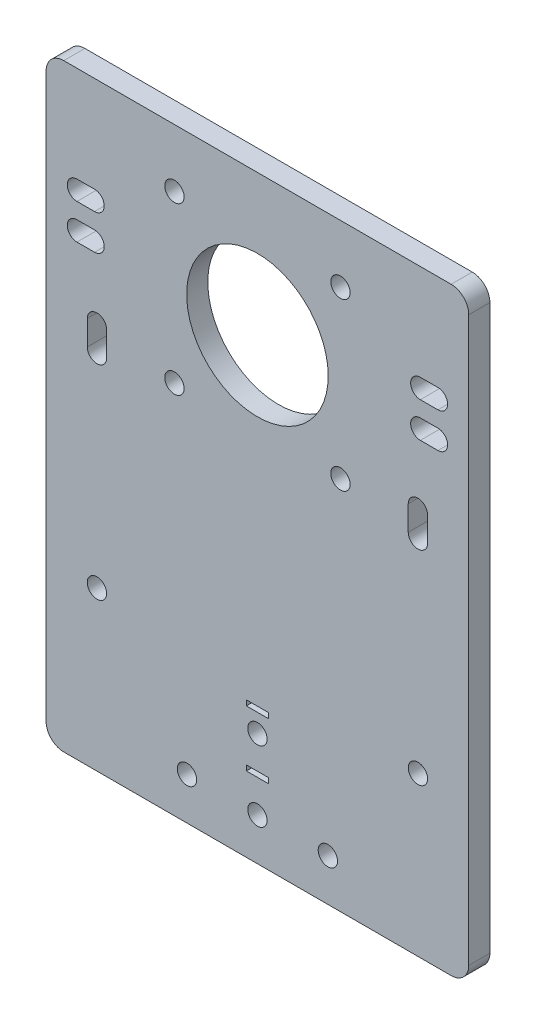
SolidWorks part; units mm, degrees
material "PET"
ref_plane "Front Plane" through (0, 0, 0) normal (0, 0, 1) x (1, 0, 0)
ref_plane "Top Plane" through (0, 0, 0) normal (0, 1, 0) x (1, 0, 0)
ref_plane "Right Plane" through (0, 0, 0) normal (1, 0, 0) x (0, 0, -1)
sketch "Sketch1" plane through (0, 0, 0) normal (0, 0, 1) x (1, 0, 0)
  line L1 (-55, -85) -> (55, -85)
  line L2 (-60, -80) -> (-60, 80)
  line L3 (-55, 85) -> (55, 85)
  line L4 (60, -80) -> (60, 80)
  line L5 (-60, -85) -> (60, 85) construction
  line L6 (-60, 85) -> (60, -85) construction
  arc A0 (-55, -85) -> (-60, -80) centre (-55, -80) cw
  arc A1 (55, -85) -> (60, -80) centre (55, -80) ccw
  arc A2 (55, 85) -> (60, 80) centre (55, 80) cw
  arc A3 (-60, 80) -> (-55, 85) centre (-55, 80) cw
  point P0 (0, 0)
  dimension "D3" = 5
  dimension "D1" = 170
  dimension "D2" = 120
extrude "Boss-Extrude1" add sketch "Sketch1" along normal blind 6
sketch "Sketch3" plane through (0, 0, 6) normal (0, 0, 1) x (1, 0, 0)
  line L0 (55, 85) -> (-55, 85) construction
  circle A0 centre (0, 45) radius 20.1
  point P6 (0, 85)
  dimension "D1" = 40
  dimension "D2" = 40.2
extrude "Cut-Extrude1" cut sketch "Sketch3" against normal blind 6
hole_wizard "M5 Clearance Hole1" positions "Sketch8" profile "Sketch9" hole size "M5" standard "ANSI Metric" end condition through all
sketch "Sketch8" plane through (0, 0, 6) normal (0, 0, 1) x (1, 0, 0)
  circle A0 centre (0, 45) radius 20.1 construction
  point P0 (-23.57, 68.57)
  point P2 (23.57, 68.57)
  point P4 (23.57, 21.43)
  point P6 (-23.57, 21.43)
  dimension "D2" = 23.57
  dimension "D3" = 23.57
  dimension "D4" = 23.57
  dimension "D5" = 23.57
  dimension "D1" = 23.57
sketch "Sketch9" plane through (-23.57, 68.57, 6) normal (1, 0, 0) x (0, -1, 0)
  line L0 (0, 0) -> (0, 6)
  line L1 (0, 6) -> (2.75, 6)
  line L2 (2.75, 6) -> (2.75, 0)
  line L5 (2.75, 0) -> (0, 0)
  line L11 (0, -6.35) -> (0, 107.95) construction
  dimension "Thru Hole Dia." = 5.5
  dimension "Thru Hole Depth" = 6
sketch "Sketch11" plane through (0, 0, 6) normal (0, 0, 1) x (1, 0, 0)
  line L0 (-45.57, 24.93) -> (-45.57, 17.93) construction
  line L1 (-42.82, 24.93) -> (-42.82, 17.93)
  line L2 (-48.32, 24.93) -> (-48.32, 17.93)
  line L5 (0, 63.1141) -> (0, -86.0691) construction
  line L8 (45.57, 24.93) -> (45.57, 17.93) construction
  line L9 (42.82, 24.93) -> (42.82, 17.93)
  line L10 (48.32, 24.93) -> (48.32, 17.93)
  arc A0 (-42.82, 24.93) -> (-48.32, 24.93) centre (-45.57, 24.93) ccw
  arc A1 (-48.32, 17.93) -> (-42.82, 17.93) centre (-45.57, 17.93) ccw
  circle A3 centre (-23.57, 21.43) radius 2.75 construction
  arc A4 (42.82, 24.93) -> (48.32, 24.93) centre (45.57, 24.93) cw
  arc A5 (48.32, 17.93) -> (42.82, 17.93) centre (45.57, 17.93) cw
  point P2 (-45.57, 21.43)
  point P15 (45.57, 21.43)
  dimension "D2" = 2.75
  dimension "D1" = 7
  dimension "D3" = 22
extrude "Cut-Extrude2" cut sketch "Sketch11" against normal blind 6
sketch "Sketch15" plane through (0, 0, 6) normal (0, 0, 1) x (1, 0, 0)
  line L0 (-51.25, 45) -> (-46.25, 45) construction
  line L1 (-51.25, 47.75) -> (-46.25, 47.75)
  line L2 (-51.25, 42.25) -> (-46.25, 42.25)
  line L3 (-51.25, 55) -> (-46.25, 55) construction
  line L4 (-51.25, 57.75) -> (-46.25, 57.75)
  line L5 (-51.25, 52.25) -> (-46.25, 52.25)
  line L6 (-60, 80) -> (-60, -80) construction
  line L8 (55, 85) -> (-55, 85) construction
  line L9 (0, 75.2932) -> (0, -13.323) construction
  line L10 (0, 63.1141) -> (0, -86.0691) construction
  line L11 (51.25, 45) -> (46.25, 45) construction
  line L12 (51.25, 47.75) -> (46.25, 47.75)
  line L13 (51.25, 42.25) -> (46.25, 42.25)
  line L14 (51.25, 55) -> (46.25, 55) construction
  line L15 (51.25, 57.75) -> (46.25, 57.75)
  line L16 (51.25, 52.25) -> (46.25, 52.25)
  arc A0 (-51.25, 47.75) -> (-51.25, 42.25) centre (-51.25, 45) ccw
  arc A1 (-46.25, 42.25) -> (-46.25, 47.75) centre (-46.25, 45) ccw
  arc A2 (-51.25, 57.75) -> (-51.25, 52.25) centre (-51.25, 55) ccw
  arc A3 (-46.25, 52.25) -> (-46.25, 57.75) centre (-46.25, 55) ccw
  arc A5 (51.25, 47.75) -> (51.25, 42.25) centre (51.25, 45) cw
  arc A6 (46.25, 42.25) -> (46.25, 47.75) centre (46.25, 45) cw
  arc A7 (51.25, 57.75) -> (51.25, 52.25) centre (51.25, 55) cw
  arc A8 (46.25, 52.25) -> (46.25, 57.75) centre (46.25, 55) cw
  point P2 (-48.75, 45)
  point P7 (-48.75, 55)
  point P15 (-54, 45)
  point P32 (48.75, 45)
  point P39 (48.75, 55)
  dimension "D1" = 30
  dimension "D2" = 2.75
  dimension "D4" = 5
  dimension "D5" = 6
  dimension "D6" = 10
extrude "Cut-Extrude4" cut sketch "Sketch15" against normal blind 6
hole_wizard "M5 Clearance Hole3" positions "Sketch17" profile "Sketch18" hole size "M5" standard "ANSI Metric" end condition through all
sketch "Sketch17" plane through (0, 0, 6) normal (0, 0, 1) x (1, 0, 0)
  line L1 (-55, -85) -> (55, -85) construction
  line L2 (60, -80) -> (60, 80) construction
  line L3 (-60, 80) -> (-60, -80) construction
  point P0 (-45.57, -39.97)
  point P2 (45.57, -39.97)
  point P4 (20, -73)
  point P6 (0, -73)
  point P8 (-20, -73)
  dimension "D3" = 40
  dimension "D1" = 61.4
  dimension "D2" = 12
  dimension "D4" = 40
sketch "Sketch18" plane through (-45.57, -39.97, 6) normal (1, 0, 0) x (0, -1, 0)
  line L0 (0, 0) -> (0, 6)
  line L1 (0, 6) -> (2.75, 6)
  line L2 (2.75, 6) -> (2.75, 0)
  line L5 (2.75, 0) -> (0, 0)
  line L11 (0, -6.35) -> (0, 107.95) construction
  dimension "Thru Hole Dia." = 5.5
  dimension "Thru Hole Depth" = 6
hole_wizard "M5 Clearance Hole2" positions "Sketch19" profile "Sketch20" hole size "M5" standard "ANSI Metric"
sketch "Sketch19" plane through (0, 0, 0) normal (0, 0, -1) x (-1, 0, 0)
  circle A0 centre (0, -73) radius 2.75 construction
  point P0 (0, -53)
  dimension "D1" = 20
sketch "Sketch20" plane through (0, -53, 0) normal (1, 0, 0) x (0, 1, 0)
  line L0 (0, 0) -> (0, 11.6524)
  line L1 (0, 11.6524) -> (2.75, 10)
  line L2 (2.75, 10) -> (2.75, 0)
  line L5 (2.75, 0) -> (0, 0)
  line L10 (0, 11.6524) -> (-2.75, 10) construction
  line L11 (0, -6.35) -> (0, 107.95) construction
  dimension "Hole Dia." = 5.5
  dimension "Hole Depth" = 10
  dimension "Drill Angle" = 118
sketch "Sketch21" plane through (0, 0, 0) normal (0, 0, -1) x (-1, 0, 0)
  line L1 (-3.15, -46.25) -> (3.15, -46.25)
  line L2 (-3.15, -46.25) -> (-3.15, -47.75)
  line L3 (-3.15, -47.75) -> (3.15, -47.75)
  line L4 (3.15, -46.25) -> (3.15, -47.75)
  line L5 (-3.15, -46.25) -> (3.15, -47.75) construction
  line L6 (-3.15, -47.75) -> (3.15, -46.25) construction
  circle A0 centre (0, -53) radius 2.75 construction
  point P0 (0, -47)
  dimension "D1" = 6.3
  dimension "D2" = 1.5
  dimension "D3" = 6
extrude "Cut-Extrude5" cut sketch "Sketch21" against normal blind 6
sketch "Sketch22" plane through (0, 0, 6) normal (0, 0, 1) x (1, 0, 0)
  line L1 (-3.15, -63.75) -> (3.15, -63.75)
  line L2 (-3.15, -63.75) -> (-3.15, -62.25)
  line L3 (-3.15, -62.25) -> (3.15, -62.25)
  line L4 (3.15, -63.75) -> (3.15, -62.25)
  line L5 (-3.15, -63.75) -> (3.15, -62.25) construction
  line L6 (-3.15, -62.25) -> (3.15, -63.75) construction
  circle A0 centre (0, -53) radius 2.75 construction
  point P0 (0, -63)
  dimension "D1" = 6.3
  dimension "D2" = 1.5
  dimension "D3" = 10
extrude "Cut-Extrude6" cut sketch "Sketch22" against normal blind 10
